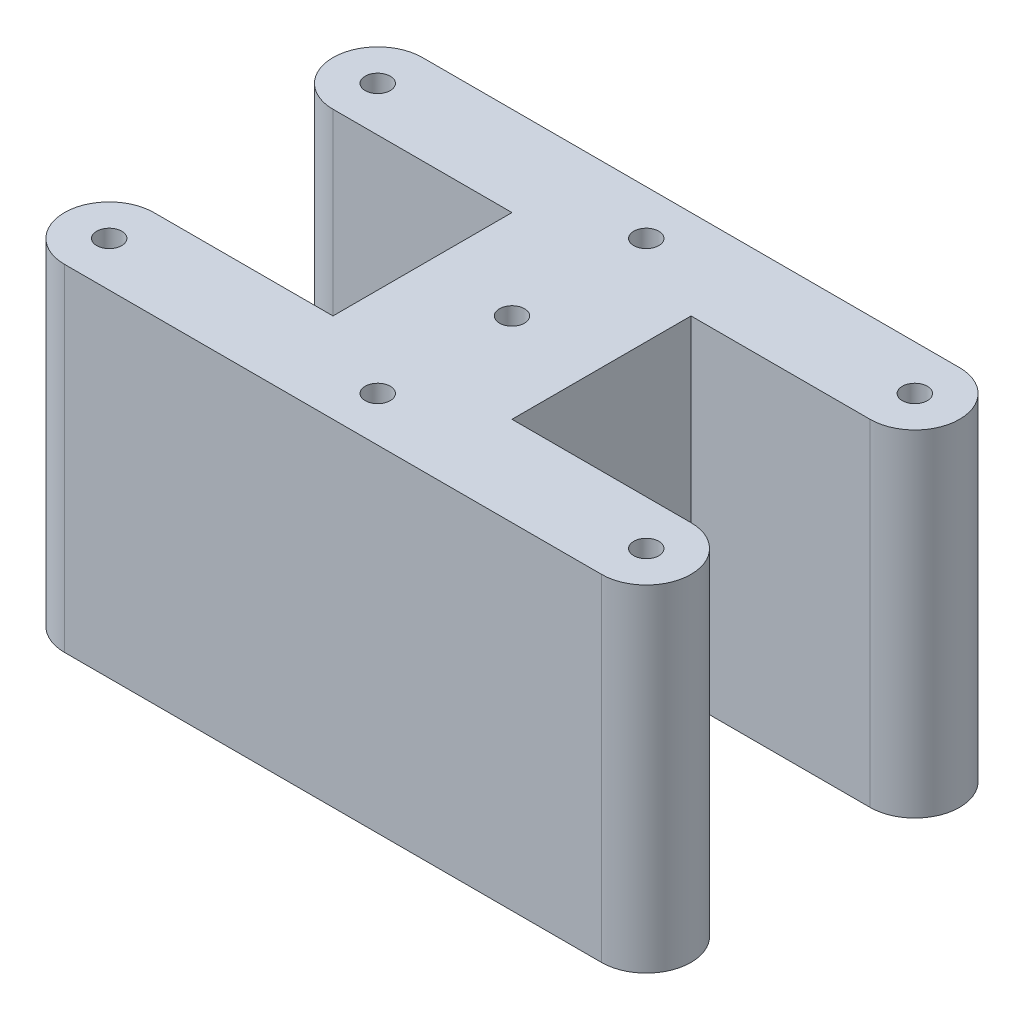
SolidWorks part; units mm, degrees
ref_plane "前视基准面" through (0, 0, 0) normal (0, 0, 1) x (1, 0, 0)
ref_plane "上视基准面" through (0, 0, 0) normal (0, 1, 0) x (1, 0, 0)
ref_plane "右视基准面" through (0, 0, 0) normal (1, 0, 0) x (0, 0, -1)
sketch "草图1" plane through (0, 0, 0) normal (0, 1, 0) x (1, 0, 0)
  line L0 (4.449, -10.8496) -> (4.449, 9.1504)
  line L4 (4.449, 9.1504) -> (24.449, 9.1504)
  line L5 (4.449, -10.8496) -> (24.449, -10.8496)
  line L6 (-35.551, 19.1504) -> (24.449, 19.1504)
  line L7 (-15.551, -10.8496) -> (-35.551, -10.8496)
  line L8 (-15.551, 9.1504) -> (-35.551, 9.1504)
  line L9 (-15.551, -10.8496) -> (-15.551, 9.1504)
  line L10 (-35.551, -20.8496) -> (24.449, -20.8496)
  circle A0 centre (24.449, 14.1504) radius 1.4
  arc A1 (24.449, 19.1504) -> (24.449, 9.1504) centre (24.449, 14.1504) cw
  arc A2 (24.449, -20.8496) -> (24.449, -10.8496) centre (24.449, -15.8496) ccw
  circle A3 centre (24.449, -15.8496) radius 1.4
  circle A4 centre (-5.551, 14.1504) radius 1.4
  circle A5 centre (-5.551, -0.8496) radius 1.4
  circle A6 centre (-5.551, -15.8496) radius 1.4
  circle A9 centre (-35.551, -15.8496) radius 1.4
  arc A10 (-35.551, -20.8496) -> (-35.551, -10.8496) centre (-35.551, -15.8496) cw
  arc A11 (-35.551, 19.1504) -> (-35.551, 9.1504) centre (-35.551, 14.1504) ccw
  circle A12 centre (-35.551, 14.1504) radius 1.4
extrude "凸台-拉伸1" add sketch "草图1" along normal blind 37.55
